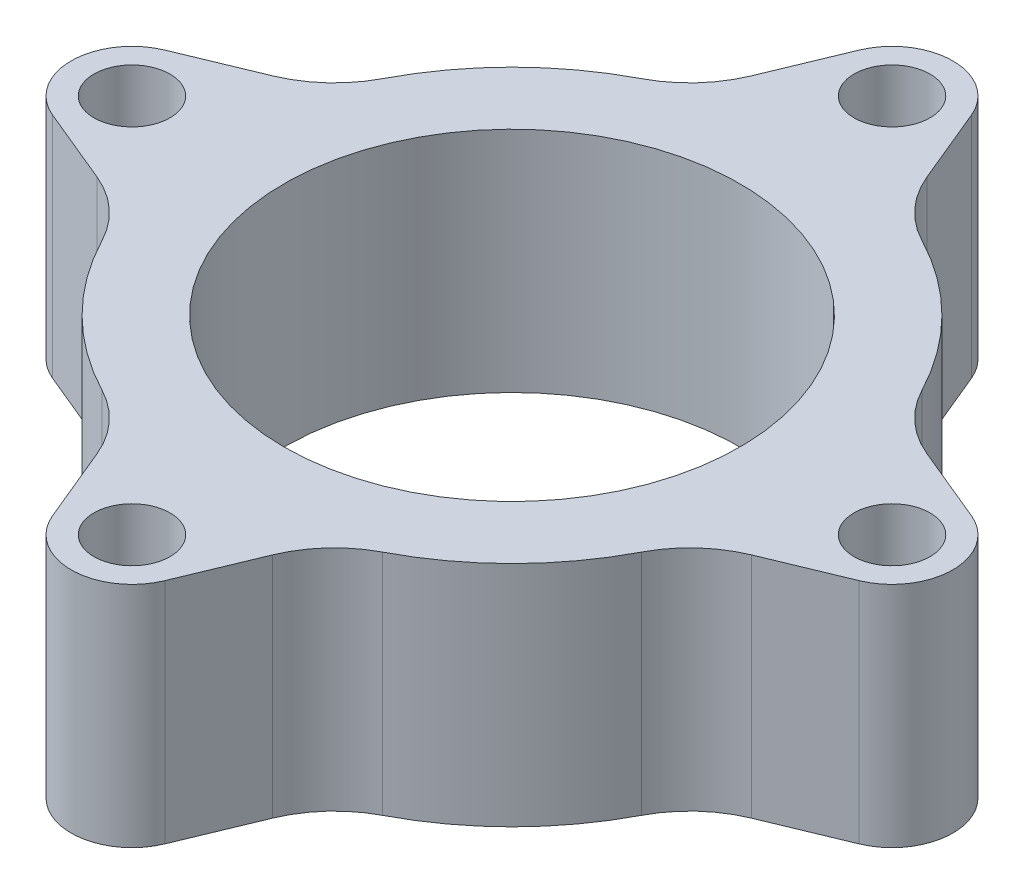
SolidWorks part; units mm, degrees
material "Plain Carbon Steel"
ref_plane "Front Plane" through (0, 0, 0) normal (0, 0, 1) x (1, 0, 0)
ref_plane "Top Plane" through (0, 0, 0) normal (0, 1, 0) x (1, 0, 0)
ref_plane "Right Plane" through (0, 0, 0) normal (1, 0, 0) x (0, 0, -1)
sketch "Sketch1" plane through (0, 0, 0) normal (0, 1, 0) x (1, 0, 0)
  line L0 (0, 132.8019) -> (0, -116.7204) construction
  line L1 (-97.1461, 0) -> (98.7072, 0) construction
  line L2 (-7.391, 53.0615) -> (-13.8219, 37.5361)
  line L3 (7.391, 53.0615) -> (13.8219, 37.5361)
  line L4 (53.0615, 7.391) -> (37.5361, 13.8219)
  line L5 (53.0615, -7.391) -> (37.5361, -13.8219)
  line L6 (7.391, -53.0615) -> (13.8219, -37.5361)
  line L7 (-7.391, -53.0615) -> (-13.8219, -37.5361)
  line L8 (-53.0615, -7.391) -> (-37.5361, -13.8219)
  line L9 (-53.0615, 7.391) -> (-37.5361, 13.8219)
  line L10 (0, 0) -> (13.8219, 37.5361) construction
  circle A0 centre (0, 0) radius 30
  arc A1 (-13.8219, 37.5361) -> (-37.5361, 13.8219) centre (0, 0) ccw
  circle A2 centre (0, 50) radius 5
  circle A4 centre (0, 50) radius 8
  circle A5 centre (50, 0) radius 8
  circle A6 centre (50, 0) radius 5
  circle A7 centre (0, -50) radius 8
  circle A8 centre (0, -50) radius 5
  circle A9 centre (-50, 0) radius 8
  circle A10 centre (-50, 0) radius 5
  arc A11 (37.5361, 13.8219) -> (13.8219, 37.5361) centre (0, 0) ccw
  arc A12 (13.8219, -37.5361) -> (37.5361, -13.8219) centre (0, 0) ccw
  arc A13 (-37.5361, -13.8219) -> (-13.8219, -37.5361) centre (0, 0) ccw
  point P16 (0, 0)
  dimension "D1" = 60
  dimension "D2" = 80
  dimension "D4" = 10
  dimension "D5" = 16
  dimension "D3" = 50
  dimension "D6" = 45
  dimension "D7" = 4
extrude "Boss-Extrude1" add sketch "Sketch1" along normal mid plane 30 contours L8 A13 L7 A7 L6 A12 L5 A5 L4 A11 L3 A4 L2 A1 L9 A9 A0 | A10 | A2 | A6 | A8
fillet "Fillet1" radius 15 8 edges at (13.8219, 0, -37.5361) (37.5361, 0, -13.8219) (37.5361, 0, 13.8219) (13.8219, 0, 37.5361) (-13.8219, 0, 37.5361) (-37.5361, 0, 13.8219) (-37.5361, 0, -13.8219) (-13.8219, 0, -37.5361)
